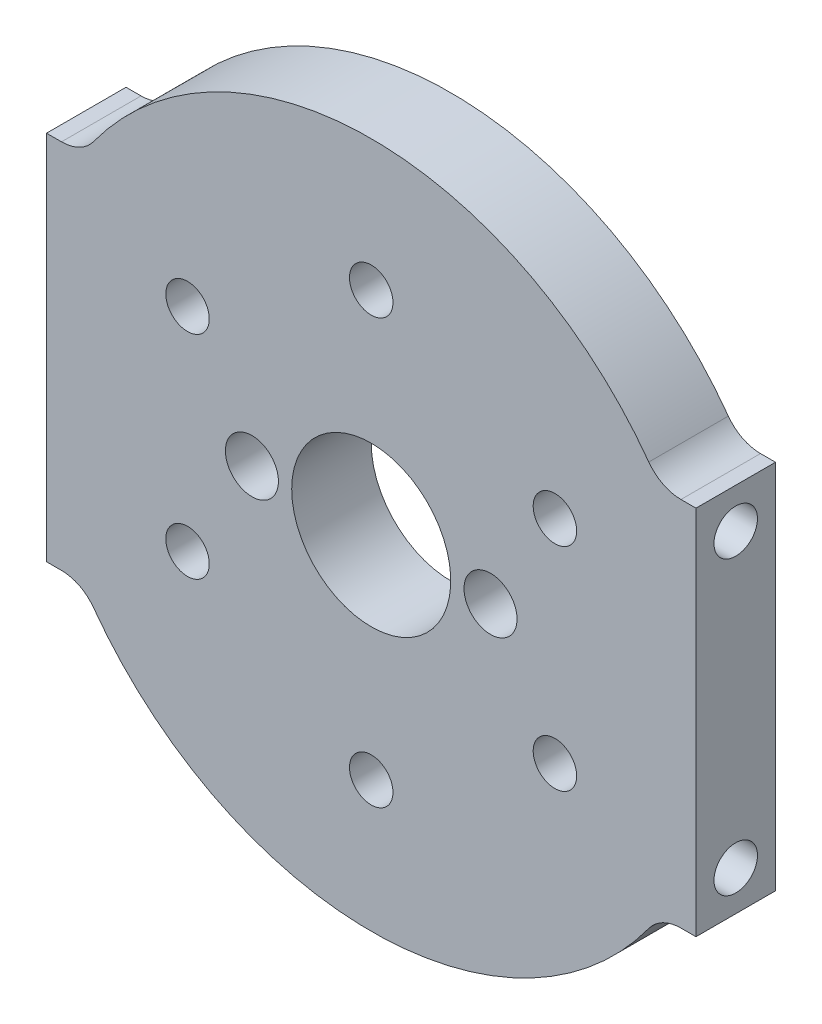
SolidWorks part; units mm, degrees
ref_plane "Front Plane" through (0, 0, 0) normal (0, 0, 1) x (1, 0, 0)
ref_plane "Top Plane" through (0, 0, 0) normal (0, 1, 0) x (1, 0, 0)
ref_plane "Right Plane" through (0, 0, 0) normal (1, 0, 0) x (0, 0, -1)
sketch "Sketch1" plane through (0, 0, 200.7267) normal (0, 0, 1) x (1, 0, 0)
  line L0 (-37.0906, 784.9811) -> (-38.8871, 784.9811)
  line L1 (0, 762.7561) -> (0, 803.8634) construction
  line L2 (-38.8871, 784.9811) -> (-38.8871, 740.5311)
  line L3 (0, 762.7561) -> (-38.8871, 762.7561) construction
  line L4 (-37.0906, 740.5311) -> (-38.8871, 740.5311)
  line L5 (37.0906, 784.9811) -> (38.8871, 784.9811)
  line L6 (38.8871, 784.9811) -> (38.8871, 740.5311)
  line L7 (37.0906, 740.5311) -> (38.8871, 740.5311)
  circle A0 centre (14.2875, 762.7561) radius 3.175 construction
  circle A1 centre (-14.2875, 762.7561) radius 3.175 construction
  circle A2 centre (0, 788.1561) radius 3.175 construction
  circle A3 centre (-21.997, 775.4561) radius 3.175 construction
  circle A4 centre (21.997, 775.4561) radius 3.175 construction
  circle A5 centre (21.997, 750.0561) radius 3.175 construction
  circle A6 centre (0, 737.3561) radius 3.175 construction
  circle A7 centre (-21.997, 750.0561) radius 3.175 construction
  circle A8 centre (14.2875, 762.7561) radius 3.175
  circle A9 centre (-14.2875, 762.7561) radius 3.175
  circle A10 centre (0, 788.1561) radius 3.175 construction
  circle A11 centre (-21.997, 775.4561) radius 3.175 construction
  circle A12 centre (21.997, 775.4561) radius 3.175 construction
  circle A13 centre (21.997, 750.0561) radius 3.175 construction
  circle A14 centre (0, 737.3561) radius 3.175 construction
  circle A15 centre (-21.997, 750.0561) radius 3.175 construction
  circle A16 centre (0, 762.7561) radius 9.525 construction
  circle A17 centre (0, 762.7561) radius 9.525
  arc A18 (33.2396, 786.9416) -> (-33.2396, 786.9416) centre (0, 762.7561) ccw
  arc A19 (-37.0906, 784.9811) -> (-33.2396, 786.9416) centre (-37.0906, 789.7436) ccw
  arc A20 (33.2396, 738.5707) -> (-33.2396, 738.5707) centre (0, 762.7561) cw
  arc A21 (-37.0906, 740.5311) -> (-33.2396, 738.5707) centre (-37.0906, 735.7686) cw
  arc A22 (37.0906, 784.9811) -> (33.2396, 786.9416) centre (37.0906, 789.7436) cw
  arc A23 (37.0906, 740.5311) -> (33.2396, 738.5707) centre (37.0906, 735.7686) ccw
  circle A24 centre (0, 788.1561) radius 2.6035
  circle A25 centre (-21.997, 775.4561) radius 2.6035
  circle A26 centre (-21.997, 750.0561) radius 2.6035
  circle A27 centre (0, 737.3561) radius 2.6035
  circle A28 centre (21.997, 750.0561) radius 2.6035
  circle A29 centre (21.997, 775.4561) radius 2.6035
  dimension "D1" = 4.7625
  dimension "D5" = 5.207
  dimension "D2" = 41.1073
  dimension "D3" = 38.8871
  dimension "D4" = 44.45
extrude "Boss-Extrude1" add sketch "Sketch1" along normal blind 9.525
sketch "Sketch2" plane through (-38.8871, 0, 0) normal (-1, 0, 0) x (0, 0, 1)
  line L0 (200.7267, 784.9811) -> (210.2517, 775.4561) construction
  line L1 (200.7267, 762.7561) -> (210.2517, 762.7561) construction
  line L4 (200.7267, 784.9811) -> (200.7267, 740.5311)
  line L5 (200.7267, 740.5311) -> (210.2517, 740.5311)
  line L6 (210.2517, 740.5311) -> (210.2517, 784.9811)
  line L7 (210.2517, 784.9811) -> (200.7267, 784.9811)
  line L8 (200.7267, 784.9811) -> (200.7267, 740.5311) construction
  line L9 (200.7267, 740.5311) -> (210.2517, 740.5311) construction
  line L10 (210.2517, 740.5311) -> (210.2517, 784.9811) construction
  line L11 (210.2517, 784.9811) -> (200.7267, 784.9811) construction
  circle A0 centre (205.4892, 780.2186) radius 2.6035
  circle A1 centre (205.4892, 745.2936) radius 2.6035
  dimension "D2" = 5.207
  dimension "D3" = 45
  dimension "D1" = 0
extrude "Cut-Extrude1" cut sketch "Sketch2" against normal blind 12.7
mirror "Mirror1" about plane through (0, 0, 0) normal (1, 0, 0) of "Cut-Extrude1"
